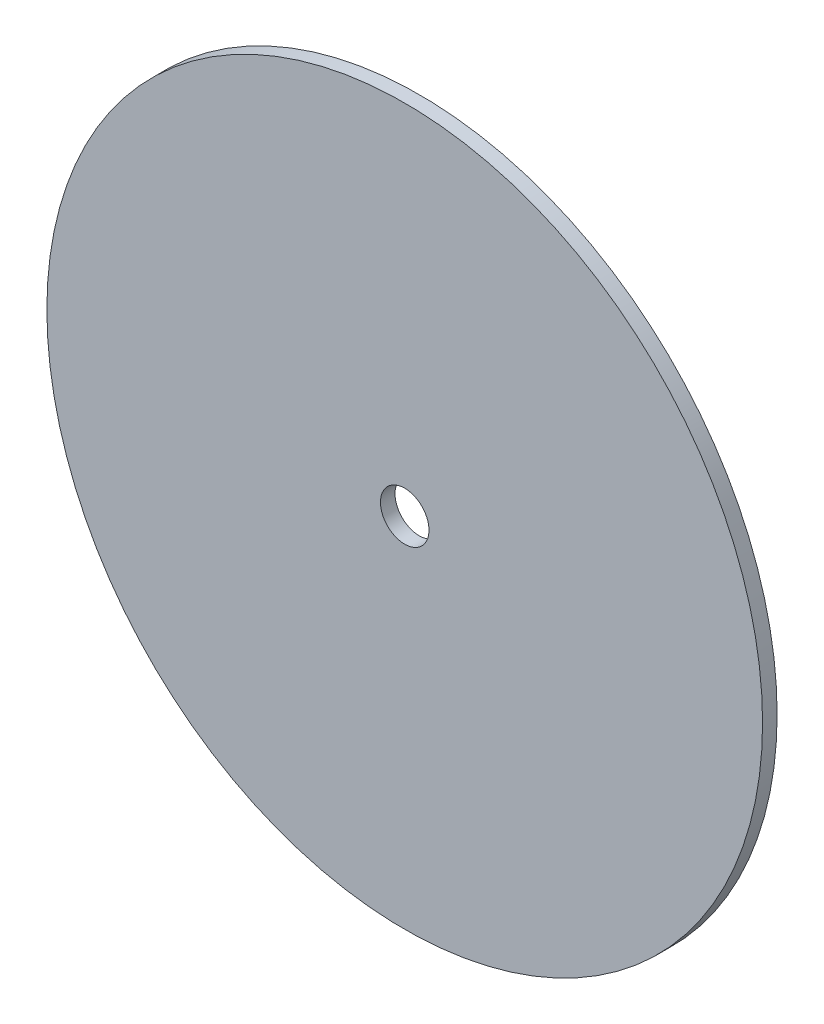
SolidWorks part; units mm, degrees
ref_plane "Front Plane" through (0, 0, 0) normal (0, 0, 1) x (1, 0, 0)
ref_plane "Top Plane" through (0, 0, 0) normal (0, 1, 0) x (1, 0, 0)
ref_plane "Right Plane" through (0, 0, 0) normal (1, 0, 0) x (0, 0, -1)
sketch "Sketch1" plane through (0, 0, 0) normal (0, 0, 1) x (1, 0, 0)
  circle A0 centre (0, 0) radius 29.5
extrude "Boss-Extrude1" add sketch "Sketch1" along normal blind 1.2
sketch "Sketch2" plane through (0, 0, 0) normal (0, 0, -1) x (-1, 0, 0)
  circle A0 centre (0, 0) radius 2
extrude "Cut-Extrude1" cut sketch "Sketch2" against normal blind 1.2 contours A0
